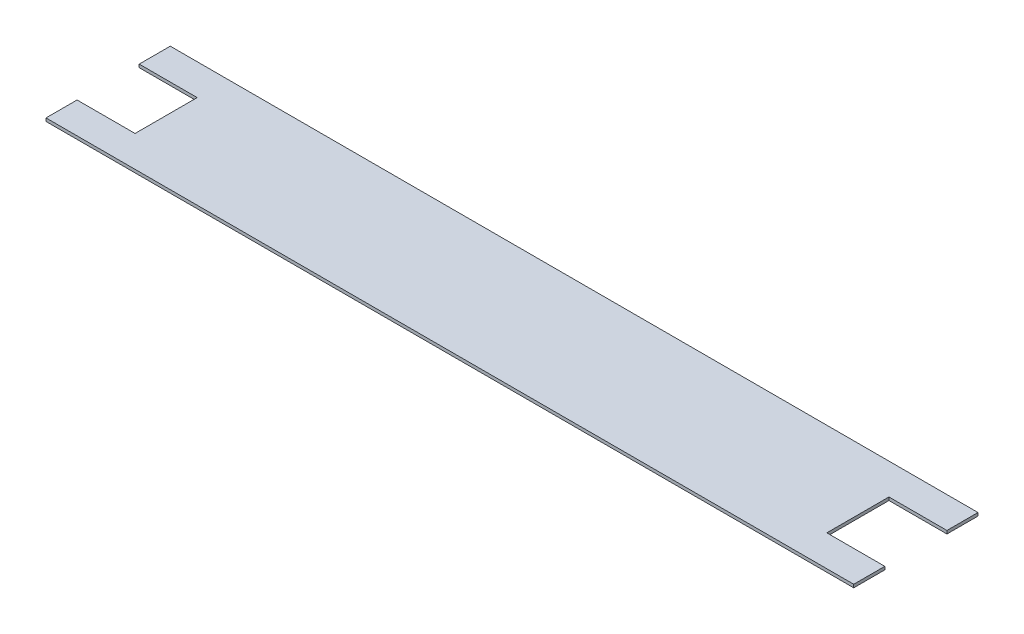
SolidWorks part; units mm, degrees
ref_plane "Спереди" through (0, 0, 0) normal (0, 0, 1) x (1, 0, 0)
ref_plane "Сверху" through (0, 0, 0) normal (0, 1, 0) x (1, 0, 0)
ref_plane "Справа" through (0, 0, 0) normal (1, 0, 0) x (0, 0, -1)
sketch "Эскиз1" plane through (0, 0, 0) normal (0, 1, 0) x (1, 0, 0)
  line L0 (0, 0) -> (0, 15)
  line L1 (0, 15) -> (28, 15)
  line L2 (28, 15) -> (28, 45)
  line L3 (28, 45) -> (0, 45)
  line L4 (0, 45) -> (0, 60)
  line L5 (0, 60) -> (390, 60)
  line L6 (390, 60) -> (390, 45)
  line L7 (390, 45) -> (362, 45)
  line L8 (362, 45) -> (362, 15)
  line L9 (362, 15) -> (390, 15)
  line L10 (390, 15) -> (390, 0)
  line L11 (390, 0) -> (0, 0)
  point P6 (390, 7.5)
  dimension "D1" = 390
  dimension "D2" = 60
  dimension "D3" = 30
  dimension "D4" = 28
extrude "Бобышка-Вытянуть1" add sketch "Эскиз1" along normal blind 1.5
